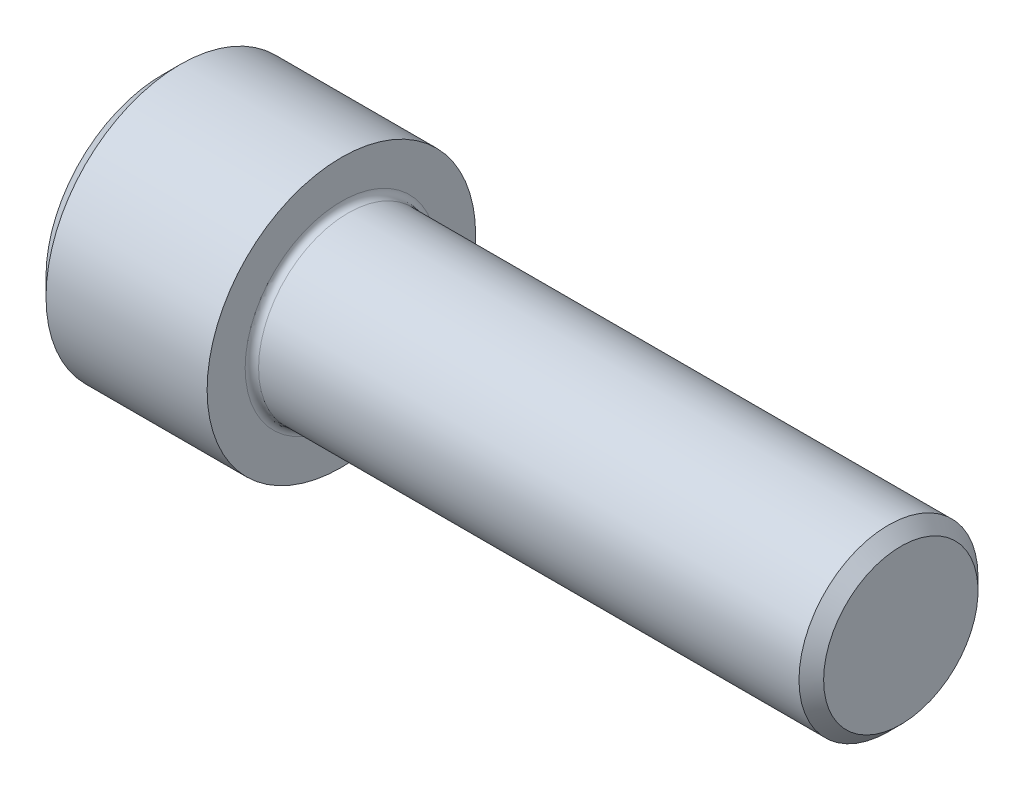
SolidWorks part; units mm, degrees
revolve "Base-Revolve" add sketch "BodySke"
sketch "BodySke" plane through (0, 0, 0) normal (0, 0, 1) x (1, 0, 0)
  line L0 (0, 0) -> (0, 10.4)
  line L1 (1.6, 12) -> (16, 12)
  line L2 (16, 12) -> (16, 8)
  line L3 (16, 8) -> (64.8985, 8)
  line L4 (66, 6.8985) -> (66, 0)
  line L5 (66, 0) -> (0, 0)
  line L6 (-31.75, 0) -> (127, 0) construction
  line L7 (0, 10.4) -> (1.6, 12)
  line L8 (66, 6.8985) -> (64.8985, 8)
  line L9 (0, -10.4) -> (1.6, -12) construction
  line L10 (66, -6.8985) -> (64.8985, -8) construction
  line L11 (18, 9.525) -> (18, 3.175) construction
  line L12 (16, 9.525) -> (16, 3.175) construction
  line L13 (16, 9.525) -> (16, 3.175) construction
  dimension "Diameter" = 16
  dimension "Head_ht" = 16
  dimension "Length" = 50
  dimension "Body_ch_ang" = 45
  dimension "Head_dia" = 24
  dimension "Head_ch_ang" = 45
  dimension "Minor_dia" = 13.797
  dimension "Advance" = 2
  dimension "Thread_nom" = 50
  dimension "Thread_length" = 50
  dimension "Head_ch_ht" = 1.6
cosmetic thread "ThreadCosmetic" [suppressed]
fillet "Fillet1" radius 0.6 1 edges at (16, 0, 8)
ref_plane "Plane1" through (0, 0, 0) normal (0, 0, 1) x (1, 0, 0)
ref_plane "Plane2" through (0, 0, 0) normal (0, 1, 0) x (1, 0, 0)
ref_plane "Plane3" through (0, 0, 0) normal (1, 0, 0) x (0, 0, -1)
sketch "Sketch2" plane through (0, 0, 0) normal (0, 0, 1) x (1, 0, 0)
  line L0 (0, 7.071) -> (8, 7.071)
  line L1 (8, 7.071) -> (12.0824, 0)
  line L2 (-31.75, 0) -> (127, 0) construction
  line L3 (12.0824, 0) -> (0, 0)
  line L4 (0, 0) -> (0, 7.071)
  line L5 (0, 10.4) -> (0, -10.4) construction
  line L6 (0, 0) -> (47.625, 0) construction
  line L7 (16, -12) -> (16, 12) construction
  dimension "D1" = 7.071
  dimension "D2" = 60
revolve "Hex-PreBroach" cut sketch "Sketch2" angle 360 about L6
sketch "Sketch3" plane through (0, 0, 0) normal (-1, 0, 0) x (0, 0.5, 0.866)
  line L0 (4.0824, 7.071) -> (-4.0824, 7.071)
  line L1 (-4.0824, 7.071) -> (-8.1649, 0)
  line L2 (4.0824, 7.071) -> (8.1649, 0)
  line L3 (4.0824, -7.071) -> (8.1649, 0)
  line L4 (4.0824, -7.071) -> (-4.0824, -7.071)
  line L5 (-4.0824, -7.071) -> (-8.1649, 0)
  dimension "D1" = 7.071
  dimension "D2" = 7.071
  dimension "Hex_size" = 14.142
extrude "Hex" cut sketch "Sketch3" against normal blind 8
sketch "Sketch4" plane through (0, 0, 0) normal (-1, 0, 0) x (0, 0, 1)
  line L0 (0, 0) -> (3.7846, 0)
  line L1 (0, 0) -> (6.1484, 3.5498) construction
  line L2 (0, 0) -> (1.8923, 3.2776)
  line L3 (3.1235, 0.8061) -> (3.6229, 1.0945)
  line L4 (2.2599, 2.3019) -> (2.7593, 2.5903)
  arc A0 (3.1235, 0.8061) -> (2.2599, 2.3019) centre (0, 0) ccw
  arc A1 (3.7846, 0) -> (3.6229, 1.0945) centre (0, 0) ccw
  arc A2 (1.8923, 3.2776) -> (2.7593, 2.5903) centre (0, 0) cw
  dimension "D1" = 30
  dimension "D2" = 60
  dimension "Spline_p_dim" = 1.7272
  dimension "D3" = 0.8636
extrude "Spline" [suppressed] cut sketch "Sketch4" against normal blind 8
pattern_circular "CirPattern1" [suppressed] count 6 every 60
sketch "Sketch5" plane through (0, 0, 0) normal (0, 0, 1) x (1, 0, 0)
  line L0 (-31.75, 0) -> (127, 0) construction
  line L2 (0, 10.4) -> (0, -10.4) construction
  circle A0 centre (5, 0) radius 0.825
  dimension "Drilled_hole_dia" = 1.65
  dimension "Drilled_hole_loc" = 5
extrude "Hole" [suppressed] cut sketch "Sketch5" against normal through all and the other way through all
pattern_circular "Drilled-4" [suppressed] count 2 every 60
pattern_circular "Drilled-6" [suppressed] count 3 every 60
sketch "ThdSchSke" plane through (0, 0, 0) normal (0, 0, 1) x (1, 0, 0)
  line L0 (18, -6.8985) -> (17.2287, -8)
  line L1 (18, -6.8985) -> (18.7713, -8)
  line L2 (18.7713, -8) -> (18.7713, -10)
  line L3 (-3.175, 0) -> (5.1513, 0) construction
  line L5 (18.7713, -10) -> (17.2287, -10)
  line L6 (17.2287, -10) -> (17.2287, -8)
  line L7 (0, 10.4) -> (0, -10.4) construction
  dimension "Thread_minor" = 13.797
  dimension "Diameter" = 16
  dimension "Start" = 18
revolve "ThreadSchematic" [suppressed] cut sketch "ThdSchSke" angle 360 about L3
pattern_linear "ThdSchPat" [suppressed]
equation "\"D2@Sketch3\" = \"Hex_size@Sketch3\" / 2"
equation "\"D1@Sketch3\" = \"Hex_size@Sketch3\" / 2"
equation "\"D1@Sketch2\" = \"Hex_size@Sketch3\" / 2"
equation "\"D3@Sketch4\" = \"Spline_p_dim@Sketch4\" / 2"
equation "\"Thread_minor@ThreadCosmetic\"  =  \"Minor_dia@BodySke\""
equation "\"D2@CirPattern1\" = 360 / \"Num_teeth@CirPattern1\""
equation "\"Wall_thickness@Sketch2\" = \"Head_ht@BodySke\" - \"Key_eng@Hex\""
equation "\"Thread_length@ThreadCosmetic\" = ((sgn( (\"Length@BodySke\" - \"Advance@BodySke\" ) - \"Thread_nom@BodySke\" )-1)*( (\"Length@BodySke\" - \"Advance@BodySke\" ) - \"Thread_nom@BodySke\" ))/-2+ \"Thread_nom@BodySke\""
equation "\"Thread_minor@ThdSchSke\" = \"Minor_dia@BodySke\""
equation "\"Diameter@ThdSchSke\" = \"Diameter@BodySke\""
equation "\"Overcut@ThdSchSke\" = \"Diameter@BodySke\" * 1.25"
equation "\"Start@ThdSchSke\" = \"Head_ht@BodySke\" + \"Length@BodySke\" - \"Thread_length@ThreadCosmetic\"  '---Non-countersunk---"
equation "\"Num_threads@ThdSchPat\" = int( \"Thread_length@ThreadCosmetic\" / \"Advance@BodySke\" + 0.999 )  + 1"
equation "\"Advance@ThdSchPat\" = \"Thread_length@ThreadCosmetic\" /  (\"Num_threads@ThdSchPat\" - 1) 'relax it"
equation "\"Num_threads@ThdSchPat\" = \"Num_threads@ThdSchPat\" - sgn( \"Num_threads@ThdSchPat\" - 1) '---chamfered tips only---"
